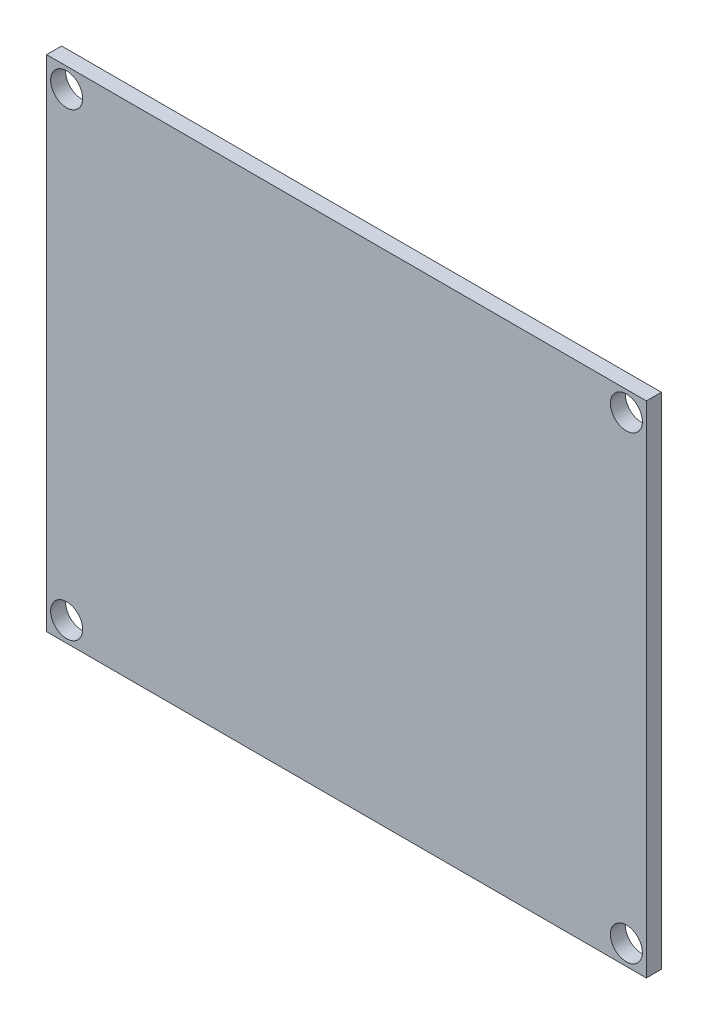
SolidWorks part; units mm, degrees
ref_plane "前视基准面" through (0, 0, 0) normal (0, 0, 1) x (1, 0, 0)
ref_plane "上视基准面" through (0, 0, 0) normal (0, 1, 0) x (1, 0, 0)
ref_plane "右视基准面" through (0, 0, 0) normal (1, 0, 0) x (0, 0, -1)
other "Configuration Table"
sketch "草图1" plane through (0, 0, 0) normal (0, 0, 1) x (1, 0, 0)
  line L0 (-28, -23) -> (-28, 23) construction
  line L1 (-30, -25) -> (30, -25)
  line L2 (-30, -25) -> (-30, 25)
  line L3 (-30, 25) -> (30, 25)
  line L4 (30, -25) -> (30, 25)
  line L5 (-30, -25) -> (30, 25) construction
  line L6 (-30, 25) -> (30, -25) construction
  line L7 (-28, 23) -> (28, 23) construction
  line L8 (28, -23) -> (28, 23) construction
  line L9 (-28, -23) -> (28, -23) construction
  circle A0 centre (28, 23) radius 1.6
  circle A1 centre (28, -23) radius 1.6
  circle A2 centre (-28, 23) radius 1.6
  circle A3 centre (-28, -23) radius 1.6
  point P0 (0, 0)
  dimension "D4" = 3.2
  dimension "D5" = 3.2
  dimension "D6" = 3.2
  dimension "D7" = 3.2
  dimension "D1" = 60
  dimension "D2" = 50
  dimension "D3" = 2
extrude "凸台-拉伸1" add sketch "草图1" along normal blind 1.5
sketch "草图2" plane through (0, 0, 1.5) normal (0, 0, 1) x (1, 0, 0)
  circle A1 centre (-25.118, -18.063) radius 1
